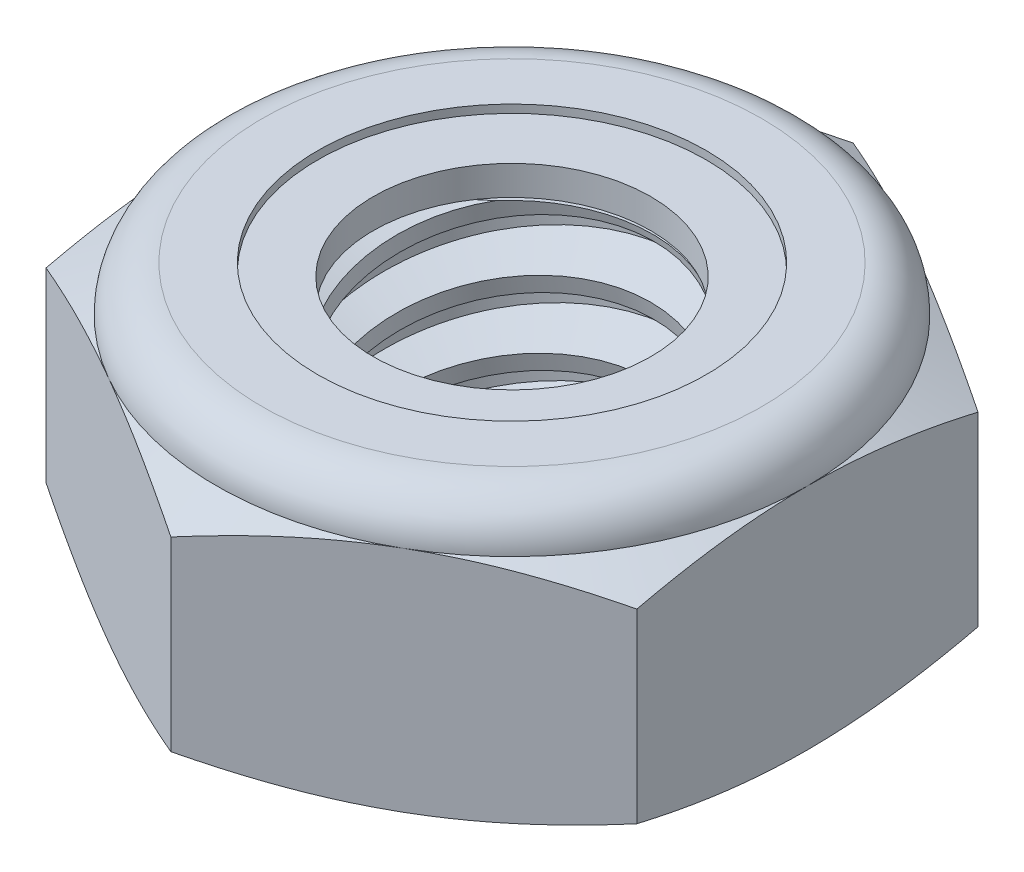
SolidWorks part; units mm, degrees
ref_plane "Front" through (0, 0, 0) normal (0, 0, 1) x (1, 0, 0)
ref_plane "Top" through (0, 0, 0) normal (0, 1, 0) x (1, 0, 0)
ref_plane "Right" through (0, 0, 0) normal (1, 0, 0) x (0, 0, -1)
sketch "Sketch1" plane through (0, 0, 0) normal (0, 1, 0) x (1, 0, 0)
  line L1 (0, 6.4158) -> (-5.5562, 3.2079)
  line L2 (-5.5562, 3.2079) -> (-5.5563, -3.2079)
  line L3 (-5.5563, -3.2079) -> (0, -6.4158)
  line L4 (0, -6.4158) -> (5.5562, -3.2079)
  line L5 (5.5562, -3.2079) -> (5.5562, 3.2079)
  line L6 (5.5562, 3.2079) -> (0, 6.4158)
  circle A0 centre (0, 0) radius 5.5563 construction
  dimension "Hex Flats" = 11.1125
extrude "Extrude1" add sketch "Sketch1" along normal blind 5.1594
sketch "Sketch2" plane through (0, 0, 0) normal (1, 0, 0) x (0, 0, -1)
  line L0 (-3.175, 0) -> (-3.175, 5.1594) construction
  line L1 (0, 0) -> (3.175, 0)
  line L2 (0, 0) -> (0, 5.1594)
  line L3 (0, 5.1594) -> (3.175, 5.1594)
  line L4 (3.175, 0) -> (3.175, 5.1594)
  line L5 (-3.2079, 5.1594) -> (3.2079, 5.1594) construction
  line L7 (0, -3.175) -> (0, 0) construction
  dimension "Thread Dia" = 6.35
revolve "Revolve1" add sketch "Sketch2" angle 360 about L7
sketch "Sketch3" plane through (0, 0, 0) normal (1, 0, 0) x (0, 0, -1)
  line L0 (3.175, 5.1594) -> (-3.175, 5.1594) construction
  line L1 (-3.175, 5.1594) -> (-3.175, 3.8894) construction
  line L2 (-3.175, 3.8894) -> (3.175, 5.1594) construction
  line L3 (3.175, 5.1594) -> (3.2061, 5.0037) construction
  line L4 (3.2061, 5.0037) -> (3.4241, 3.914)
  line L5 (3.4241, 3.914) -> (2.6722, 4.1684)
  line L6 (2.6722, 4.1684) -> (2.6099, 4.4797)
  line L7 (2.6099, 4.4797) -> (3.2061, 5.0037)
  line L8 (2.641, 4.3241) -> (3.3151, 4.4589) construction
  line L9 (3.175, 5.1594) -> (3.175, 4.4309) construction
  line L10 (3.175, 4.4309) -> (-3.175, 3.1609) construction
  line L11 (-3.175, 3.1609) -> (-3.175, 3.8894) construction
  line L12 (-0.2727, 5.1594) -> (0.2727, 2.4323) construction
  line L13 (-3.175, 0) -> (-3.175, 5.1594) construction
  line L14 (0, 5.1594) -> (3.175, 5.1594) construction
  line L15 (3.175, 0) -> (3.175, 5.1594) construction
  point P13 (0, 3.7959)
  dimension "D1" = 0.1588
  dimension "D2" = 0.3175
  dimension "Thread Pitch" = 1.27
  dimension "D4" = 60
  dimension "D5" = 1.27
revolve "Cut-Revolve1" cut sketch "Sketch3" angle 360 about L12
pattern_linear "LPattern1" count 4 spacing 1.27 along (0, -1, 0) count 2 spacing 1.27 along (0, 1, 0) of "Cut-Revolve1"
sketch "Sketch4" plane through (0, 0, 0) normal (1, 0, 0) x (0, 0, -1)
  line L0 (0, 5.1594) -> (3.175, 5.1594)
  line L1 (3.175, 5.1594) -> (2.6099, 4.8959)
  line L2 (2.6099, 4.8959) -> (2.6099, 0.2635)
  line L3 (2.6099, 0.2635) -> (3.175, 0)
  line L4 (3.175, 0) -> (0, 0)
  line L5 (0, 0) -> (0, 5.1594)
  line L6 (3.175, 0) -> (3.175, 5.1594) construction
  line L7 (0, 5.1594) -> (3.175, 5.1594) construction
  line L8 (0, 0) -> (3.175, 0) construction
  line L9 (0, 0) -> (0, 5.1594) construction
  line L10 (0, 5.1594) -> (0, 5.7829) construction
  dimension "D1" = 25
revolve "Cut-Revolve2" cut sketch "Sketch4" angle 360 about L10
combine bodies "Combine1" operation type subtract main body 112 bodies to subtract 111
sketch "Sketch5" plane through (0, 0, 0) normal (1, 0, 0) x (0, 0, -1)
  line L0 (0, 0) -> (5.5563, 0)
  line L1 (5.5563, 0) -> (6.4158, 0.4008)
  line L2 (6.4158, 0.4008) -> (6.4158, 3.8987)
  line L3 (6.4158, 3.8987) -> (5.5563, 4.2995)
  line L4 (4.6964, 5.1594) -> (4.6964, 6.4294)
  line L5 (4.6964, 6.4294) -> (7.6858, 6.4294)
  line L6 (7.6858, 6.4294) -> (7.6858, -1.27)
  line L7 (7.6858, -1.27) -> (0, -1.27)
  line L8 (0, -1.27) -> (0, 0)
  line L9 (5.5563, 4.2995) -> (5.5563, 0) construction
  line L10 (0, 0) -> (3.175, 0) construction
  line L13 (6.4158, 2.1497) -> (7.6858, 2.1497) construction
  line L14 (6.4158, 5.1594) -> (6.4158, 0) construction
  line L15 (0, 0) -> (0, 6.4294) construction
  line L20 (0, 6.4294) -> (4.6964, 6.4294) construction
  line L22 (0, 5.1594) -> (3.175, 5.1594) construction
  arc A0 (5.5563, 4.2995) -> (4.6964, 5.1594) centre (4.6964, 4.2995) ccw
  dimension "D1" = 25
  dimension "D2" = 1.27
  dimension "D3" = 5.1594
  dimension "D4" = 0.8599
revolve "Cut-Revolve3" cut sketch "Sketch5" angle 360 about L15
sketch "Sketch6" plane through (0, 0, 0) normal (1, 0, 0) x (0, 0, -1)
  line L0 (0, 4.2995) -> (5.4039, 4.2995)
  line L1 (4.6964, 5.007) -> (3.6531, 5.007)
  line L2 (0, 6.4294) -> (0, 4.2995)
  line L3 (3.6531, 6.4294) -> (0, 6.4294)
  line L4 (0, 6.4294) -> (4.6964, 6.4294) construction
  line L5 (0, 0) -> (0, 6.4294) construction
  line L6 (0, 6.4294) -> (0, 44.323) construction
  line L7 (3.6531, 5.007) -> (3.6531, 6.4294)
  line L8 (4.6964, 5.1594) -> (4.6964, 5.007) construction
  line L9 (3.6531, 5.007) -> (2.6099, 5.007) construction
  line L10 (2.6099, 5.007) -> (2.6099, 4.8959) construction
  arc A0 (5.4039, 4.2995) -> (4.6964, 5.007) centre (4.6964, 4.2995) ccw
  arc A1 (5.5563, 4.2995) -> (4.6964, 5.1594) centre (4.6964, 4.2995) ccw construction
  dimension "D1" = 0.1524
revolve "Cut-Revolve4" cut sketch "Sketch6" angle 360 about L6
sketch "Sketch7" plane through (0, 0, 0) normal (1, 0, 0) x (0, 0, -1)
  line L0 (2.6099, 4.3757) -> (5.323, 4.3757)
  line L1 (4.6964, 4.9308) -> (2.6099, 4.9308)
  line L2 (2.6099, 4.9308) -> (2.6099, 4.3757)
  line L3 (2.6099, 4.3757) -> (0, 4.3757) construction
  line L4 (0, 4.3757) -> (0, 4.9308) construction
  line L5 (0, 4.9308) -> (2.6099, 4.9308) construction
  line L6 (2.6099, 4.3757) -> (2.6099, 4.2995) construction
  line L7 (0, 4.2995) -> (5.4039, 4.2995) construction
  line L8 (4.6964, 4.9308) -> (4.6964, 5.007) construction
  arc A0 (5.323, 4.3757) -> (4.6964, 4.9308) centre (4.6964, 4.2995) ccw
  arc A2 (5.4039, 4.2995) -> (4.6964, 5.007) centre (4.6964, 4.2995) ccw construction
  dimension "D1" = 0.0762
revolve "Revolve2" add sketch "Sketch7" angle 360 about L4
equation "\"D1@Sketch3\"=\"Thread Pitch@Sketch3\"/8"
equation "\"D2@Sketch3\"=\"Thread Pitch@Sketch3\"/4"
equation "\"D5@Sketch3\"=\"Thread Pitch@Sketch3\""
equation "\"D4@LPattern1\"=\"Thread Pitch@Sketch3\""
equation "\"D3@LPattern1\"=\"Thread Pitch@Sketch3\""
equation "\"D1@LPattern1\"=\"Height@Extrude1\"/\"Thread Pitch@Sketch3\""
equation "\"D4@Sketch5\"=\"Height@Extrude1\"/6"
